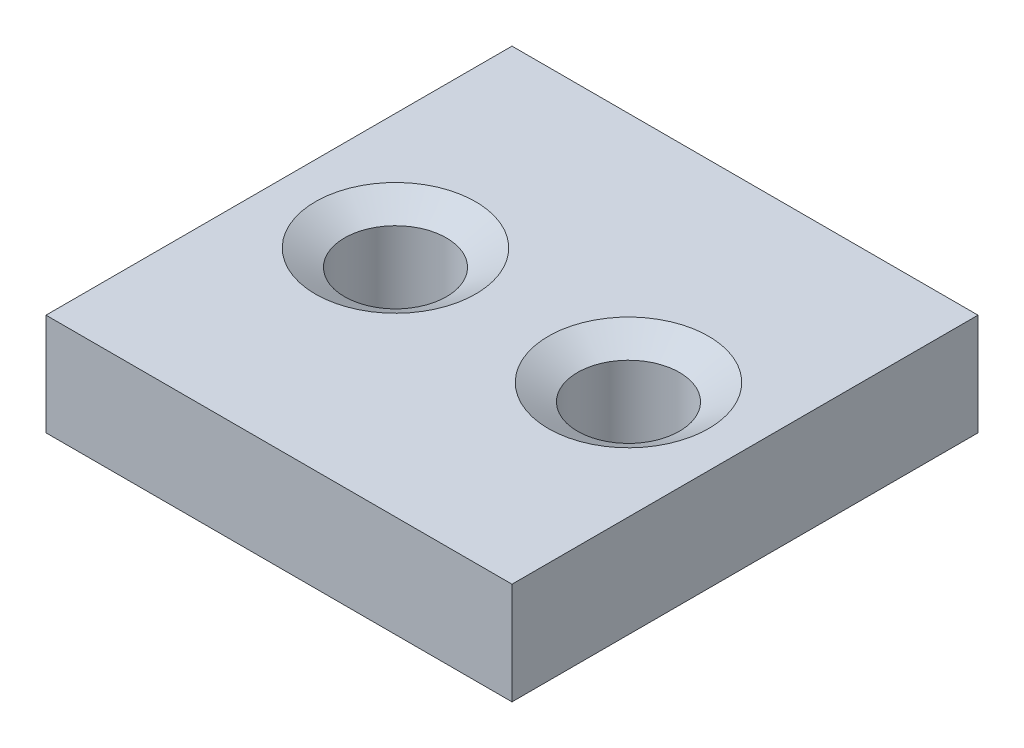
SolidWorks part; units mm, degrees
material "AISI 1045 Steel, cold drawn"
ref_plane "Front Plane" through (0, 0, 0) normal (0, 0, 1) x (1, 0, 0)
ref_plane "Top Plane" through (0, 0, 0) normal (0, 1, 0) x (1, 0, 0)
ref_plane "Right Plane" through (0, 0, 0) normal (1, 0, 0) x (0, 0, -1)
sketch "Sketch1" plane through (0, 0, 0) normal (0, 1, 0) x (1, 0, 0)
  line L1 (-16, 16) -> (16, 16)
  line L2 (-16, 16) -> (-16, -16)
  line L3 (-16, -16) -> (16, -16)
  line L4 (16, 16) -> (16, -16)
  line L5 (0, -16) -> (0, 16) construction
  line L6 (-16, 0) -> (16, 0) construction
  circle A0 centre (-8, 0) radius 3.5
  circle A1 centre (8, 0) radius 3.5
  point P0 (0, 0)
  dimension "D3" = 7
  dimension "D4" = 7
  dimension "D1" = 32
  dimension "D2" = 32
  dimension "D5" = 8
  dimension "D6" = 16
extrude "Boss-Extrude1" add sketch "Sketch1" along normal blind 7
chamfer "Chamfer2" distance 2 angle 30 2 edges at (8, 7, 3.5) (-8, 7, 3.5)
